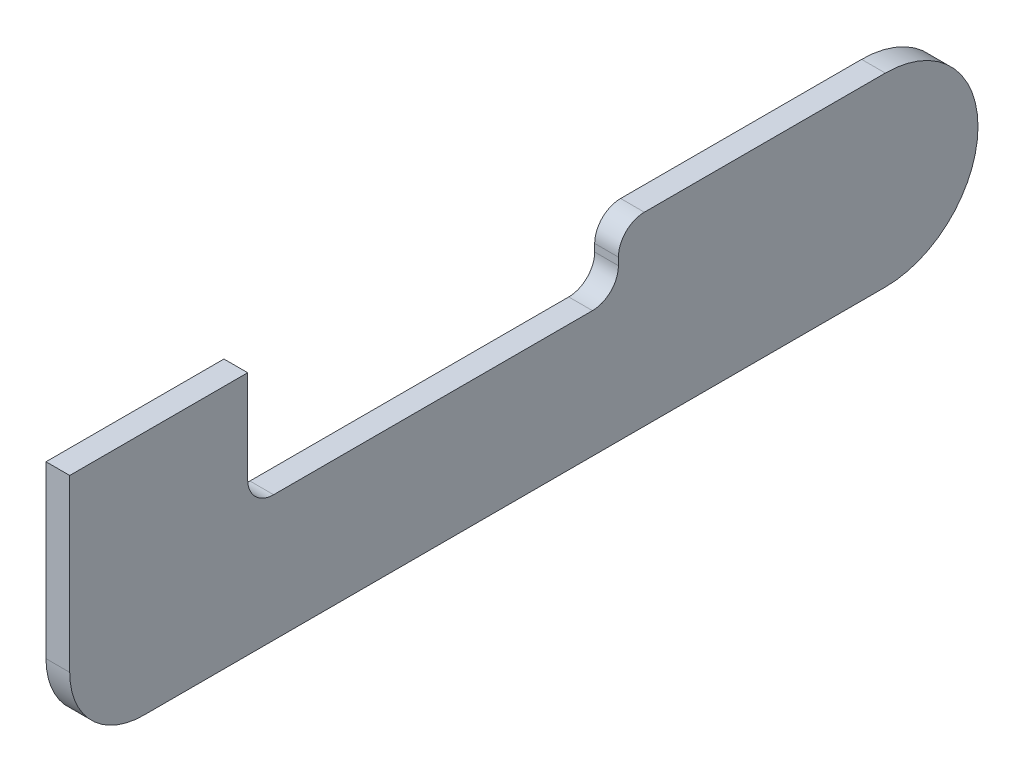
SolidWorks part; units mm, degrees
ref_plane "Ebene vorne" through (0, 0, 0) normal (0, 0, 1) x (1, 0, 0)
ref_plane "Ebene oben" through (0, 0, 0) normal (0, 1, 0) x (1, 0, 0)
ref_plane "Ebene rechts" through (0, 0, 0) normal (1, 0, 0) x (0, 0, -1)
sketch "Skizze1" plane through (0, 0, 0) normal (1, 0, 0) x (0, 0, -1)
  line L0 (95, -12.5) -> (45, -12.5)
  line L1 (22.6244, 0) -> (27.1602, 0)
  line L2 (27.1602, 0) -> (27.1602, -2.5041)
  line L3 (53.0864, 0) -> (53.0864, -2.5)
  line L4 (27.1602, 0) -> (27.1602, 4)
  line L5 (40, -4) -> (40, -7.5)
  line L6 (27.1602, 4) -> (53.0864, 4)
  line L7 (53.0864, 4) -> (53.0864, 0)
  line L8 (40, 4) -> (52, 4)
  line L9 (52, 4) -> (52, -2.25)
  line L10 (40, 4) -> (40, -4)
  line L11 (53.75, -4) -> (75.25, -4)
  line L12 (95, 0) -> (78.75, 0)
  line L13 (77, -1.75) -> (77, -2.25)
  arc A0 (95, -12.5) -> (95, 0) centre (95, -6.25) ccw
  arc A1 (45, -12.5) -> (40, -7.5) centre (45, -7.5) cw
  arc A2 (52, -2.25) -> (53.75, -4) centre (53.75, -2.25) ccw
  arc A3 (78.75, 0) -> (77, -1.75) centre (78.75, -1.75) ccw
  arc A4 (75.25, -4) -> (77, -2.25) centre (75.25, -2.25) ccw
  point P1 (0, 0)
  point P11 (0, 0)
  point P12 (40.1233, 4)
  point P26 (52, -4)
  point P31 (77, -4)
  dimension "D1" = 12.5
  dimension "D10" = 5
  dimension "D11" = 1.75
  dimension "D2" = 4
  dimension "D3" = 95
  dimension "D4" = 6.25
  dimension "D5" = 25.9262
  dimension "D6" = 40
  dimension "D7" = 52
  dimension "D8" = 8
  dimension "D9" = 25
extrude "Aufsatz-Linear austragen1" add sketch "Skizze1" along normal blind 1.6 contours A4 L11 A2 L9 L6 L10 L5 A1 L0 A0 L12 A3 L13
